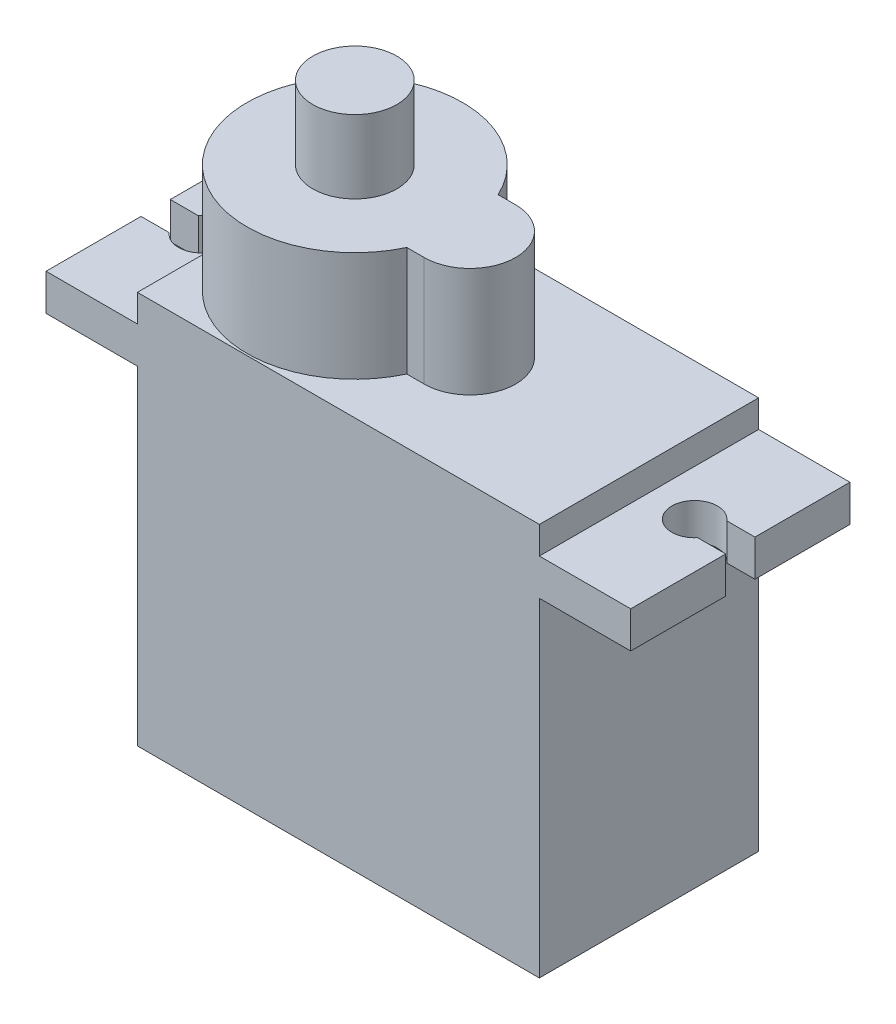
SolidWorks part; units mm, degrees
ref_plane "前视基准面" through (0, 0, 0) normal (0, 0, 1) x (1, 0, 0)
ref_plane "上视基准面" through (0, 0, 0) normal (0, 1, 0) x (1, 0, 0)
ref_plane "右视基准面" through (0, 0, 0) normal (1, 0, 0) x (0, 0, -1)
sketch "草图1" plane through (0, 0, 0) normal (0, 0, 1) x (1, 0, 0)
  line L0 (0, 0) -> (22, 0)
  line L1 (0, 18) -> (0, 0)
  line L2 (0, 20) -> (0, 21.5)
  line L3 (0, 18) -> (-5, 18)
  line L4 (22, 18) -> (22, 0)
  line L5 (22, 18) -> (27, 18)
  line L6 (-5, 18) -> (-5, 20)
  line L7 (-5, 20) -> (0, 20)
  line L8 (27, 20) -> (27, 18)
  line L9 (0, 21.5) -> (22, 21.5)
  line L10 (22, 21.5) -> (22, 20)
  line L11 (22, 20) -> (27, 20)
  dimension "D1" = 22
  dimension "D2" = 1.5
  dimension "D3" = 18
  dimension "D4" = 5
  dimension "D5" = 2
  dimension "D6" = 5
extrude "凸台-拉伸1" add sketch "草图1" along normal blind 12
sketch "草图2" plane through (0, 21.5, 0) normal (0, 1, 0) x (1, 0, 0)
  line L4 (12.2, -3.5) -> (11.2442, -3.5)
  line L5 (12.2, -8.5) -> (11.2442, -8.5)
  arc A0 (11.2442, -3.5) -> (11.2442, -8.5) centre (5.9, -6) ccw
  arc A1 (12.2, -8.5) -> (12.2, -3.5) centre (12.2, -6) ccw
  circle A2 centre (5.9, -6) radius 2.3
  dimension "D3" = 5
  dimension "D4" = 4.6
  dimension "D2" = 6.3
extrude "凸台-拉伸2" add sketch "草图2" along normal blind 6
sketch "草图3" plane through (0, 21.5, 0) normal (0, 1, 0) x (1, 0, 0)
  circle A0 centre (5.9, -6) radius 2.3
extrude "凸台-拉伸3" add sketch "草图3" along normal blind 10
sketch "草图4" plane through (0, 20, 0) normal (0, 1, 0) x (1, 0, 0)
  line L0 (22, -6) -> (24.5, -6)
  line L1 (22, -12) -> (22, 0) construction
  line L2 (0, -6) -> (-2.5, -6)
  line L3 (0, -12) -> (0, 0) construction
  line L4 (27, -5.2) -> (27, -6.8)
  line L5 (-5, -12) -> (-5, 0) construction
  line L6 (27, -12) -> (27, 0) construction
  line L7 (-5, -5.2) -> (-5, -6.8)
  line L8 (-5, -5.2) -> (-3.4605, -5.2)
  line L9 (-5, -6.8) -> (-3.4605, -6.8)
  line L11 (27, -5.2) -> (25.4605, -5.2)
  line L12 (27, -6.8) -> (25.4605, -6.8)
  arc A0 (25.4605, -5.2) -> (25.4605, -6.8) centre (24.5, -6) ccw
  arc A1 (-3.4605, -6.8) -> (-3.4605, -5.2) centre (-2.5, -6) ccw
  dimension "D2" = 2.5
  dimension "D4" = 2.5
  dimension "D1" = 2.5
  dimension "D3" = 2.5
extrude "切除-拉伸1" cut sketch "草图4" against normal up to next
